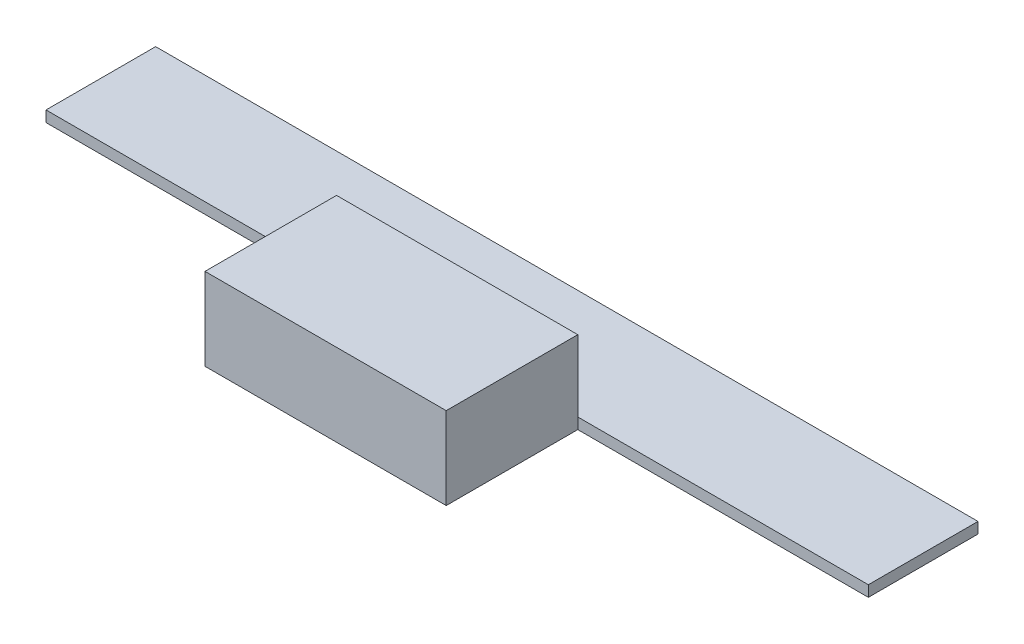
SolidWorks part; units mm, degrees
ref_plane "Front Plane" through (0, 0, 0) normal (0, 0, 1) x (1, 0, 0)
ref_plane "Top Plane" through (0, 0, 0) normal (0, 1, 0) x (1, 0, 0)
ref_plane "Right Plane" through (0, 0, 0) normal (1, 0, 0) x (0, 0, -1)
sketch "Sketch5" plane through (0, 0, 0) normal (0, 1, 0) x (1, 0, 0)
  line L1 (-22, -12) -> (22, -12)
  line L2 (-22, -12) -> (-22, 12)
  line L3 (-22, 12) -> (22, 12)
  line L4 (22, -12) -> (22, 12)
  line L5 (-22, -12) -> (22, 12) construction
  line L6 (-22, 12) -> (22, -12) construction
  point P0 (0, 0)
  dimension "D1" = 44
  dimension "D2" = 24
extrude "Boss-Extrude3" add sketch "Sketch5" along normal blind 15
shell "Shell1" thickness 2
sketch "Sketch7" plane through (-20, 0, 0) normal (1, 0, 0) x (0, 0, -1)
  line L0 (12, 13) -> (10, 13)
  line L1 (12, 13) -> (12, 1.9824)
  line L2 (10, 13) -> (10, 1.9824)
  line L3 (12, 1.9824) -> (10, 1.9824)
  line L4 (12, 13) -> (-10, 13) construction
  dimension "D1" = 2
extrude "Boss-Extrude4" add sketch "Sketch7" along normal blind 10
ref_plane "Plane1" through (0, 0, 0) normal (1, 0, 0) x (0, 0, -1)
mirror "Mirror1" about plane through (0, 0, 0) normal (1, 0, 0) of "Boss-Extrude4"
sketch "Sketch9" plane through (0, 0, -12) normal (0, 0, -1) x (-1, 0, 0)
  line L0 (-10, 2) -> (10, 2) construction
  line L1 (-75, 0) -> (75, 0)
  line L2 (-75, 0) -> (-75, 2)
  line L3 (-75, 2) -> (75, 2)
  line L4 (75, 0) -> (75, 2)
  line L5 (-22, 0) -> (22, 0) construction
  point P8 (0, 0)
  dimension "D1" = 150
extrude "Boss-Extrude5" add sketch "Sketch9" along normal blind 20
sketch "Sketch20" plane through (0, 13, 0) normal (0, -1, 0) x (1, 0, 0)
  line L0 (-10, -10) -> (10, -10)
  line L1 (10, -10) -> (10, -12)
  line L2 (10, -12) -> (-10, -12)
  line L3 (-10, -12) -> (-10, -10)
